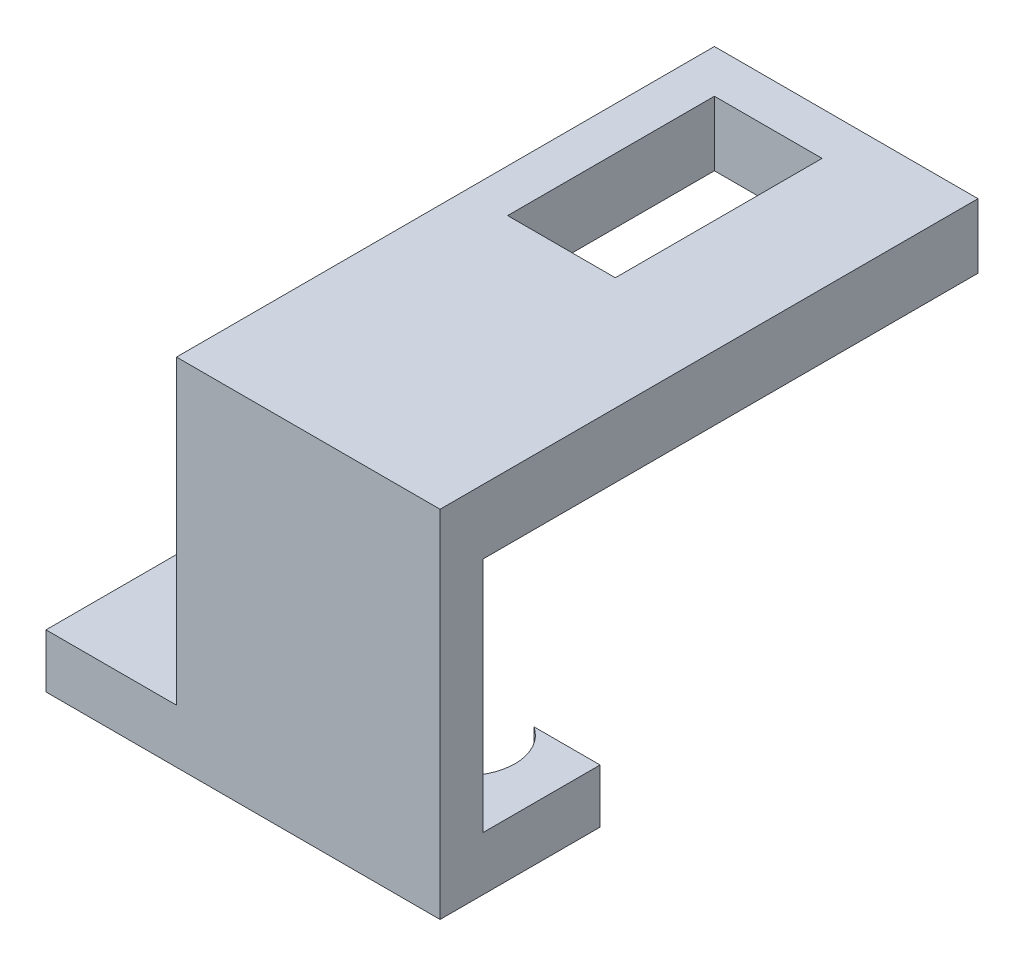
SolidWorks part; units mm, degrees
ref_plane "Front Plane" through (0, 0, 0) normal (0, 0, 1) x (1, 0, 0)
ref_plane "Top Plane" through (0, 0, 0) normal (0, 1, 0) x (1, 0, 0)
ref_plane "Right Plane" through (0, 0, 0) normal (1, 0, 0) x (0, 0, -1)
sketch "Sketch1" plane through (0, 0, 0) normal (0, 1, 0) x (1, 0, 0)
  line L0 (-4.825, 0) -> (4.825, 0) construction
  line L2 (-9.15, -3.5) -> (-9.15, 1.9307)
  line L4 (9.15, -3.5) -> (9.15, 1.9307)
  line L5 (-9.15, -3.5) -> (9.15, 3.5) construction
  line L6 (-5.6313, 2.154) -> (9.15, -3.5) construction
  line L8 (-0.575, 1.9307) -> (-0.575, -2.2811)
  line L9 (-0.575, -2.2811) -> (0.575, -2.2811)
  line L10 (0.575, -2.2811) -> (0.575, 1.9307)
  line L12 (-6.075, 1.9307) -> (-3.575, 1.9307) construction
  line L13 (3.575, 1.9307) -> (6.075, 1.9307) construction
  line L14 (-6.075, 1.9307) -> (-9.15, 1.9307)
  line L15 (-3.575, 1.9307) -> (-0.575, 1.9307)
  line L16 (6.075, 1.9307) -> (9.15, 1.9307)
  line L17 (0.575, 1.9307) -> (3.575, 1.9307)
  line L18 (-9.15, -3.5) -> (-9.15, -5.5)
  line L19 (-9.15, -5.5) -> (9.15, -5.5)
  line L20 (9.15, -5.5) -> (9.15, -3.5)
  arc A0 (3.575, 1.9307) -> (6.075, 1.9307) centre (4.825, 0) ccw
  arc A1 (-6.075, 1.9307) -> (-3.575, 1.9307) centre (-4.825, 0) ccw
  point P1 (0, 0)
  point P9 (0, 0)
  point P12 (9.15, -5.3239)
  point P14 (0, 3.5)
  dimension "D2" = 4.6
  dimension "D3" = 4.6
  dimension "D1" = 9.65
  dimension "D4" = 2
  dimension "D5" = 18.3
  dimension "D7" = 2.5
extrude "Boss-Extrude1" add sketch "Sketch1" along normal blind 2.5
sketch "Sketch2" plane through (0, 2.5, 0) normal (0, 1, 0) x (1, 0, 0)
  line L0 (-9.15, 1.9307) -> (-9.15, -5.5) construction
  line L1 (9.15, -5.5) -> (-9.15, -5.5)
  line L2 (9.15, -5.5) -> (9.15, -3.5)
  line L3 (9.15, -3.5) -> (-9.15, -3.5)
  line L4 (-9.15, -5.5) -> (-9.15, -3.5)
  dimension "D1" = 2
extrude "Boss-Extrude2" add sketch "Sketch2" along normal blind 14
sketch "Sketch3" plane through (0, 0, 3.5) normal (0, 0, -1) x (-1, 0, 0)
  line L0 (9.15, 16.5) -> (9.15, 2.5) construction
  line L1 (9.15, 13.5) -> (-9.15, 13.5)
  line L2 (9.15, 13.5) -> (9.15, 16.5)
  line L3 (9.15, 16.5) -> (-9.15, 16.5)
  line L4 (-9.15, 13.5) -> (-9.15, 16.5)
  dimension "D1" = 3
extrude "Boss-Extrude3" add sketch "Sketch3" along normal blind 22.98
sketch "Sketch4" plane through (0, 16.5, 0) normal (0, 1, 0) x (1, 0, 0)
  line L0 (-9.15, 10.6903) -> (-3.09, 10.6903) construction
  line L1 (-9.15, 19.48) -> (-9.15, -5.5) construction
  line L2 (-9.15, 17.48) -> (9.15, 17.48) construction
  line L3 (9.15, -5.5) -> (9.15, 19.48) construction
  line L4 (-9.15, 19.48) -> (9.15, 19.48) construction
  line L5 (-3.09, 10.6903) -> (-1.09, 10.6903) construction
  line L6 (-9.15, -5.5) -> (9.15, -5.5) construction
  line L7 (-1.09, 7.8777) -> (3.91, 7.8777)
  line L8 (-1.09, 7.8777) -> (-1.09, 17.48)
  line L9 (-1.09, 17.48) -> (3.91, 17.48) construction
  line L10 (3.91, 7.8777) -> (3.91, 17.48)
  line L11 (-3.09, -3.5) -> (5.91, -3.5) construction
  line L12 (-3.09, -3.5) -> (-3.09, 19.48)
  line L13 (-3.09, 19.48) -> (5.91, 19.48) construction
  line L15 (-3.09, -3.5) -> (-9.15, -3.5)
  line L16 (-9.15, -3.5) -> (-9.15, 19.48)
  line L17 (-9.15, 19.48) -> (-3.09, 19.48)
  line L22 (-1.09, 17.48) -> (3.91, 17.48)
  dimension "D1" = 6.06
  dimension "D2" = 2
  dimension "D3" = 2
  dimension "D5" = 2
  dimension "D6" = 5
  dimension "D7" = 9.6023
extrude "Cut-Extrude1" cut sketch "Sketch4" against normal up to surface (3 mm away) up to face at (0, 13.5, -7.99)
sketch "Sketch5" plane through (0, 0, 5.5) normal (0, 0, 1) x (1, 0, 0)
  line L0 (-9.15, 16.5) -> (9.15, 16.5) construction
  line L1 (-9.15, 2.5) -> (-3.09, 2.5)
  line L2 (-9.15, 2.5) -> (-9.15, 16.5)
  line L3 (-9.15, 16.5) -> (-3.09, 16.5)
  line L4 (-3.09, 2.5) -> (-3.09, 16.5)
  line L5 (-9.15, 0) -> (9.15, 0) construction
  dimension "D1" = 6.06
  dimension "D2" = 2.5
extrude "Cut-Extrude2" cut sketch "Sketch5" against normal up to surface (2 mm away) up to face at (-1.03, 10.8333, 3.5)
